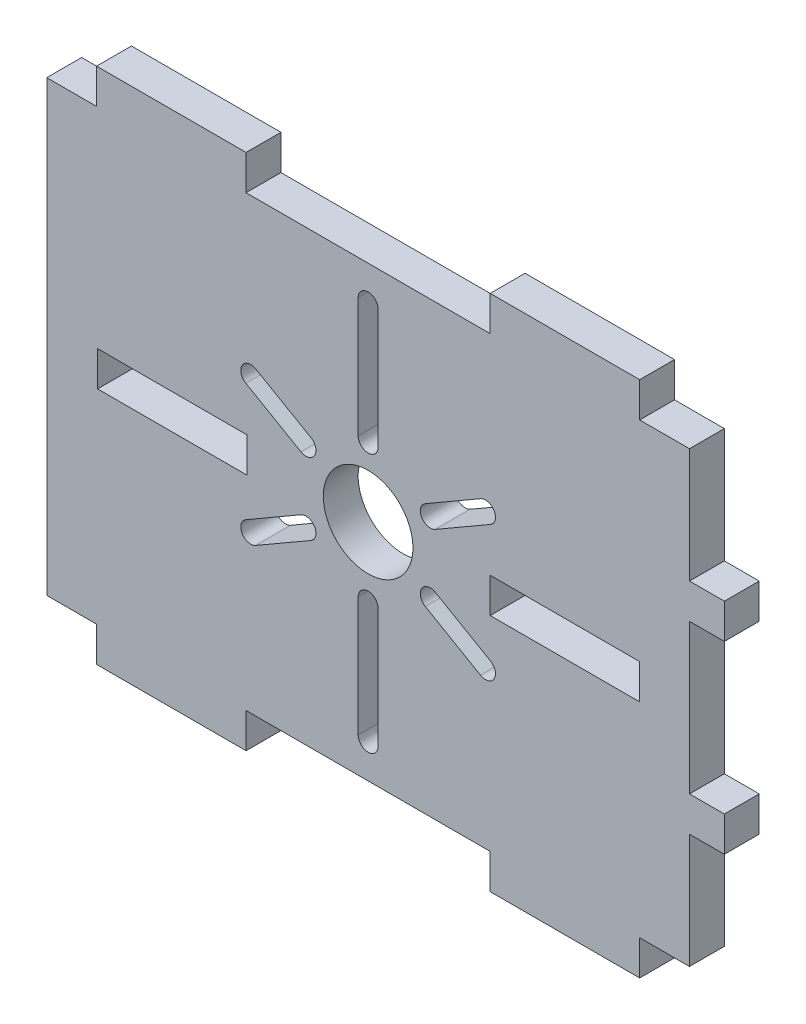
SolidWorks part; units mm, degrees
material "Balsa"
ref_plane "Front Plane" through (0, 0, 0) normal (0, 0, 1) x (1, 0, 0)
ref_plane "Top Plane" through (0, 0, 0) normal (0, 1, 0) x (1, 0, 0)
ref_plane "Right Plane" through (0, 0, 0) normal (1, 0, 0) x (0, 0, -1)
sketch "Sketch1" plane through (0, 0, 0) normal (0, 0, 1) x (1, 0, 0)
  line L0 (27.25, -26) -> (27.25, -22.5)
  line L1 (-32.25, -26) -> (32.25, -26) construction
  line L2 (-32.25, -26) -> (-32.25, 26) construction
  line L3 (-32.25, 26) -> (32.25, 26) construction
  line L4 (32.25, -26) -> (32.25, 26) construction
  line L5 (0, 26) -> (0, -26) construction
  line L6 (-32.25, 0) -> (32.25, 0) construction
  line L7 (27.25, -22.5) -> (32.25, -22.5)
  line L8 (-27.25, -26) -> (-27.25, -22.5)
  line L9 (-27.25, -22.5) -> (-32.25, -22.5)
  line L10 (27.25, 22.5) -> (32.25, 22.5)
  line L11 (27.25, 26) -> (27.25, 22.5)
  line L12 (-27.25, 26) -> (-27.25, 22.5)
  line L13 (-27.25, 22.5) -> (-32.25, 22.5)
  line L14 (12.25, -22.5) -> (-12.25, -22.5)
  line L15 (12.25, -22.5) -> (12.25, -26)
  line L16 (-12.25, -22.5) -> (-12.25, -26)
  line L17 (12.25, 22.5) -> (12.25, 26)
  line L18 (12.25, 22.5) -> (-12.25, 22.5)
  line L19 (-12.25, 22.5) -> (-12.25, 26)
  line L20 (-12.25, -26) -> (-27.25, -26)
  line L21 (-32.25, -22.5) -> (-32.25, 22.5)
  line L22 (-27.25, 26) -> (-12.25, 26)
  line L23 (12.25, 26) -> (27.25, 26)
  line L24 (32.25, 22.5) -> (32.25, 11)
  line L25 (27.25, -26) -> (12.25, -26)
  line L26 (32.25, 11) -> (35.75, 11)
  line L27 (35.75, 11) -> (35.75, 7.5)
  line L28 (35.75, 7.5) -> (32.25, 7.5)
  line L29 (35.75, -7.5) -> (32.25, -7.5)
  line L30 (35.75, -11) -> (35.75, -7.5)
  line L31 (32.25, -11) -> (35.75, -11)
  line L32 (32.25, 7.5) -> (32.25, -7.5)
  line L33 (32.25, -11) -> (32.25, -22.5)
  line L34 (0, 19) -> (0, 7) construction
  line L37 (-11.2771, -7.6675) -> (-5.7345, -4.4675)
  line L40 (1, 19) -> (1, 7)
  line L41 (-1, 19) -> (-1, 7)
  line L47 (-12.2788, -5.9325) -> (-6.7362, -2.7325)
  line L48 (-11.7779, -6.8) -> (-6.2354, -3.6) construction
  line L49 (-12.2788, 5.9325) -> (-6.7362, 2.7325)
  line L50 (-11.2771, 7.6675) -> (-5.7345, 4.4675)
  line L51 (-11.7779, 6.8) -> (-6.2354, 3.6) construction
  line L54 (0, -19) -> (0, -7) construction
  line L55 (11.2771, 7.6675) -> (5.7345, 4.4675)
  line L56 (12.2788, 5.9325) -> (6.7362, 2.7325)
  line L57 (11.7779, 6.8) -> (6.2354, 3.6) construction
  line L58 (12.2788, -5.9325) -> (6.7362, -2.7325)
  line L59 (11.2771, -7.6675) -> (5.7345, -4.4675)
  line L60 (11.7779, -6.8) -> (6.2354, -3.6) construction
  line L63 (1, -19) -> (1, -7)
  line L64 (-1, -19) -> (-1, -7)
  circle A2 centre (0, 0) radius 4.5
  arc A7 (1, 19) -> (-1, 19) centre (0, 19) ccw
  arc A8 (-1, 7) -> (1, 7) centre (0, 7) ccw
  circle A11 centre (0, -10.4) radius 0.75 construction
  circle A12 centre (0, -10.4) radius 0.75 construction
  circle A13 centre (0, -7.2) radius 0.75 construction
  circle A16 centre (0, -13.6) radius 0.75 construction
  circle A17 centre (0, -13.6) radius 0.75 construction
  circle A18 centre (0, -7.2) radius 0.75 construction
  circle A19 centre (-9.0067, -5.2) radius 0.75 construction
  arc A20 (-12.2788, -5.9325) -> (-11.2771, -7.6675) centre (-11.7779, -6.8) ccw
  arc A21 (-5.7345, -4.4675) -> (-6.7362, -2.7325) centre (-6.2354, -3.6) ccw
  circle A22 centre (-9.0067, 5.2) radius 0.75 construction
  arc A23 (-11.2771, 7.6675) -> (-12.2788, 5.9325) centre (-11.7779, 6.8) ccw
  arc A24 (-6.7362, 2.7325) -> (-5.7345, 4.4675) centre (-6.2354, 3.6) ccw
  circle A25 centre (0, 10.4) radius 0.75 construction
  circle A28 centre (9.0067, 5.2) radius 0.75 construction
  arc A29 (12.2788, 5.9325) -> (11.2771, 7.6675) centre (11.7779, 6.8) ccw
  arc A30 (5.7345, 4.4675) -> (6.7362, 2.7325) centre (6.2354, 3.6) ccw
  circle A31 centre (9.0067, -5.2) radius 0.75 construction
  arc A32 (11.2771, -7.6675) -> (12.2788, -5.9325) centre (11.7779, -6.8) ccw
  arc A33 (6.7362, -2.7325) -> (5.7345, -4.4675) centre (6.2354, -3.6) ccw
  arc A36 (1, -19) -> (-1, -19) centre (0, -19) cw
  arc A37 (-1, -7) -> (1, -7) centre (0, -7) cw
  point P0 (0, 0)
  point P36 (0, -22.5)
  point P39 (0, 13)
  point P62 (0, -13)
  point P71 (-9.0067, -5.2)
  point P80 (-9.0067, 5.2)
  point P98 (9.0067, 5.2)
  point P107 (9.0067, -5.2)
  point P112 (0, 0)
  dimension "D6" = 9
  dimension "D11" = 1
  dimension "D1" = 64.5
  dimension "D2" = 52
  dimension "D3" = 3.5
  dimension "D4" = 5
  dimension "D5" = 15
  dimension "D7" = 3.5
  dimension "D8" = 3.5
  dimension "D9" = 15
  dimension "D10" = 12
  dimension "D12" = 13
  dimension "D13" = 6
extrude "Boss-Extrude1" add sketch "Sketch1" along normal blind 3.5
sketch "Sketch2" plane through (0, 0, 0) normal (0, 0, -1) x (-1, 0, 0)
  line L0 (-12.25, 22.5) -> (12.25, 22.5) construction
  line L1 (32.25, 1.5) -> (-35.75, 1.5) construction
  line L2 (32.25, 1.5) -> (32.25, -2) construction
  line L3 (32.25, -2) -> (-35.75, -2) construction
  line L4 (-35.75, 1.5) -> (-35.75, -2) construction
  line L5 (-35.75, 7.5) -> (-35.75, 11) construction
  line L6 (32.25, 22.5) -> (32.25, -22.5) construction
  line L7 (-32.25, -7.5) -> (-32.25, 7.5) construction
  line L8 (27.15, -2) -> (12.15, -2)
  line L9 (27.15, -2) -> (27.15, 1.5)
  line L10 (27.15, 1.5) -> (12.15, 1.5)
  line L11 (12.15, -2) -> (12.15, 1.5)
  line L12 (-27.25, 1.5) -> (-12.25, 1.5)
  line L13 (-27.25, 1.5) -> (-27.25, -2)
  line L14 (-27.25, -2) -> (-12.25, -2)
  line L15 (-12.25, 1.5) -> (-12.25, -2)
  dimension "D1" = 21
  dimension "D2" = 3.5
  dimension "D3" = 15
  dimension "D4" = 5
  dimension "D5" = 5.1
extrude "Cut-Extrude1" cut sketch "Sketch2" against normal through all
